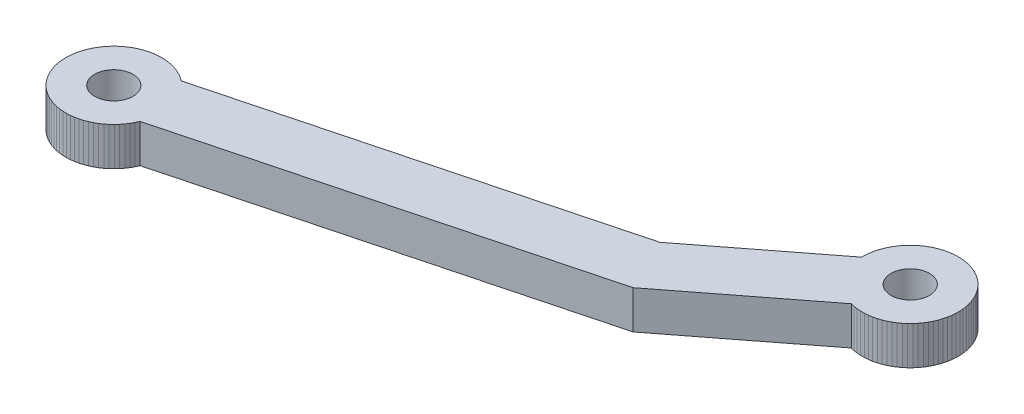
SolidWorks part; units mm, degrees
ref_plane "Спереди" through (0, 0, 0) normal (0, 0, 1) x (1, 0, 0)
ref_plane "Сверху" through (0, 0, 0) normal (0, 1, 0) x (1, 0, 0)
ref_plane "Справа" through (0, 0, 0) normal (1, 0, 0) x (0, 0, -1)
ref_plane "Плоскость4" through (0, -23, 0) normal (0, -1, 0) x (1, 0, 0)
sketch "Эскиз1" plane through (0, -23, 0) normal (0, -1, 0) x (1, 0, 0)
  line L0 (-84.0281, -2.2024) -> (-83.8528, -2.288)
  line L1 (-83.8528, -2.288) -> (-83.6713, -2.3596)
  line L2 (-83.6713, -2.3596) -> (-83.4847, -2.4168)
  line L3 (-83.4847, -2.4168) -> (-83.2943, -2.4593)
  line L4 (-83.2943, -2.4593) -> (-83.1011, -2.4869)
  line L5 (-83.1011, -2.4869) -> (-82.9064, -2.4993)
  line L6 (-82.9064, -2.4993) -> (-82.7113, -2.4964)
  line L7 (-82.7113, -2.4964) -> (-82.517, -2.4784)
  line L8 (-82.517, -2.4784) -> (-82.3248, -2.4452)
  line L9 (-82.3248, -2.4452) -> (-82.1357, -2.3972)
  line L10 (-82.1357, -2.3972) -> (-81.9509, -2.3346)
  line L11 (-81.9509, -2.3346) -> (-81.7715, -2.2577)
  line L12 (-81.7715, -2.2577) -> (-81.5987, -2.1671)
  line L13 (-81.5987, -2.1671) -> (-81.4335, -2.0633)
  line L14 (-81.4335, -2.0633) -> (-81.2769, -1.9469)
  line L15 (-81.2769, -1.9469) -> (-81.1299, -1.8187)
  line L16 (-81.1299, -1.8187) -> (-80.9933, -1.6794)
  line L17 (-80.9933, -1.6794) -> (-80.8679, -1.5298)
  line L18 (-80.8679, -1.5298) -> (-80.7546, -1.371)
  line L19 (-80.7546, -1.371) -> (-80.6541, -1.2038)
  line L20 (-80.6541, -1.2038) -> (-80.5669, -1.0292)
  line L21 (-80.5669, -1.0292) -> (-80.4936, -0.8484)
  line L22 (-80.4936, -0.8484) -> (-80.4346, -0.6624)
  line L23 (-80.4346, -0.6624) -> (-80.3902, -0.4724)
  line L24 (-80.3902, -0.4724) -> (-80.3609, -0.2795)
  line L25 (-80.3609, -0.2795) -> (-80.3466, -0.0849)
  line L26 (-80.3466, -0.0849) -> (-80.3476, 0.1102)
  line L27 (-80.3476, 0.1102) -> (-80.3638, 0.3046)
  line L28 (-80.3638, 0.3046) -> (-80.3951, 0.4972)
  line L29 (-80.3951, 0.4972) -> (-80.4414, 0.6868)
  line L30 (-80.4414, 0.6868) -> (-80.5022, 0.8721)
  line L31 (-80.5022, 0.8721) -> (-80.5774, 1.0522)
  line L32 (-80.5774, 1.0522) -> (-80.6664, 1.2258)
  line L33 (-80.6664, 1.2258) -> (-80.7686, 1.392)
  line L34 (-80.7686, 1.392) -> (-80.8835, 1.5497)
  line L35 (-80.8835, 1.5497) -> (-81.0103, 1.698)
  line L36 (-81.0103, 1.698) -> (-81.1483, 1.8359)
  line L37 (-81.1483, 1.8359) -> (-81.2967, 1.9627)
  line L38 (-81.2967, 1.9627) -> (-81.4544, 2.0774)
  line L39 (-81.4544, 2.0774) -> (-81.6207, 2.1796)
  line L40 (-81.6207, 2.1796) -> (-81.7944, 2.2684)
  line L41 (-81.7944, 2.2684) -> (-81.9745, 2.3435)
  line L42 (-81.9745, 2.3435) -> (-82.1599, 2.4042)
  line L43 (-82.1599, 2.4042) -> (-82.3495, 2.4504)
  line L44 (-82.3495, 2.4504) -> (-82.5421, 2.4816)
  line L45 (-82.5421, 2.4816) -> (-82.7365, 2.4976)
  line L46 (-82.7365, 2.4976) -> (-82.9317, 2.4985)
  line L47 (-82.9317, 2.4985) -> (-83.1262, 2.4842)
  line L48 (-83.1262, 2.4842) -> (-83.3191, 2.4547)
  line L49 (-83.3191, 2.4547) -> (-83.5091, 2.4102)
  line L50 (-83.5091, 2.4102) -> (-89.9237, 7.3733)
  line L51 (-89.9237, 7.3733) -> (-110.2847, 12.7181)
  line L52 (-110.2847, 12.7181) -> (-110.3653, 12.8958)
  line L53 (-110.3653, 12.8958) -> (-110.4595, 13.0666)
  line L54 (-110.4595, 13.0666) -> (-110.5667, 13.2296)
  line L55 (-110.5667, 13.2296) -> (-110.6864, 13.3838)
  line L56 (-110.6864, 13.3838) -> (-110.8177, 13.5281)
  line L57 (-110.8177, 13.5281) -> (-110.9598, 13.6618)
  line L58 (-110.9598, 13.6618) -> (-111.1119, 13.7839)
  line L59 (-111.1119, 13.7839) -> (-111.2731, 13.8939)
  line L60 (-111.2731, 13.8939) -> (-111.4424, 13.9909)
  line L61 (-111.4424, 13.9909) -> (-111.6187, 14.0744)
  line L62 (-111.6187, 14.0744) -> (-111.8011, 14.1439)
  line L63 (-111.8011, 14.1439) -> (-111.9882, 14.199)
  line L64 (-111.9882, 14.199) -> (-112.1791, 14.2393)
  line L65 (-112.1791, 14.2393) -> (-112.3726, 14.2647)
  line L66 (-112.3726, 14.2647) -> (-112.5674, 14.2748)
  line L67 (-112.5674, 14.2748) -> (-112.7625, 14.2697)
  line L68 (-112.7625, 14.2697) -> (-112.9565, 14.2495)
  line L69 (-112.9565, 14.2495) -> (-113.1484, 14.2141)
  line L70 (-113.1484, 14.2141) -> (-113.337, 14.1639)
  line L71 (-113.337, 14.1639) -> (-113.521, 14.0992)
  line L72 (-113.521, 14.0992) -> (-113.6995, 14.0203)
  line L73 (-113.6995, 14.0203) -> (-113.8712, 13.9277)
  line L74 (-113.8712, 13.9277) -> (-114.0352, 13.822)
  line L75 (-114.0352, 13.822) -> (-114.1905, 13.7038)
  line L76 (-114.1905, 13.7038) -> (-114.3361, 13.5739)
  line L77 (-114.3361, 13.5739) -> (-114.4711, 13.4331)
  line L78 (-114.4711, 13.4331) -> (-114.5947, 13.2821)
  line L79 (-114.5947, 13.2821) -> (-114.7061, 13.1219)
  line L80 (-114.7061, 13.1219) -> (-114.8048, 12.9536)
  line L81 (-114.8048, 12.9536) -> (-114.89, 12.7781)
  line L82 (-114.89, 12.7781) -> (-114.9612, 12.5964)
  line L83 (-114.9612, 12.5964) -> (-115.0181, 12.4098)
  line L84 (-115.0181, 12.4098) -> (-115.0602, 12.2193)
  line L85 (-115.0602, 12.2193) -> (-115.0874, 12.0261)
  line L86 (-115.0874, 12.0261) -> (-115.0994, 11.8313)
  line L87 (-115.0994, 11.8313) -> (-115.0961, 11.6362)
  line L88 (-115.0961, 11.6362) -> (-115.0777, 11.442)
  line L89 (-115.0777, 11.442) -> (-115.0442, 11.2498)
  line L90 (-115.0442, 11.2498) -> (-114.9958, 11.0608)
  line L91 (-114.9958, 11.0608) -> (-114.9328, 10.8761)
  line L92 (-114.9328, 10.8761) -> (-114.8556, 10.6969)
  line L93 (-114.8556, 10.6969) -> (-114.7646, 10.5243)
  line L94 (-114.7646, 10.5243) -> (-114.6605, 10.3593)
  line L95 (-114.6605, 10.3593) -> (-114.5438, 10.2029)
  line L96 (-114.5438, 10.2029) -> (-114.4153, 10.0561)
  line L97 (-114.4153, 10.0561) -> (-114.2757, 9.9198)
  line L98 (-114.2757, 9.9198) -> (-114.1259, 9.7947)
  line L99 (-114.1259, 9.7947) -> (-113.9668, 9.6818)
  line L100 (-113.9668, 9.6818) -> (-113.7994, 9.5815)
  line L101 (-113.7994, 9.5815) -> (-113.6247, 9.4947)
  line L102 (-113.6247, 9.4947) -> (-113.4438, 9.4217)
  line L103 (-113.4438, 9.4217) -> (-113.2577, 9.3631)
  line L104 (-113.2577, 9.3631) -> (-113.0676, 9.3191)
  line L105 (-113.0676, 9.3191) -> (-112.8746, 9.2902)
  line L106 (-112.8746, 9.2902) -> (-112.68, 9.2763)
  line L107 (-112.68, 9.2763) -> (-112.4849, 9.2777)
  line L108 (-112.4849, 9.2777) -> (-112.2905, 9.2943)
  line L109 (-112.2905, 9.2943) -> (-112.098, 9.326)
  line L110 (-112.098, 9.326) -> (-111.9085, 9.3726)
  line L111 (-111.9085, 9.3726) -> (-111.7232, 9.4338)
  line L112 (-111.7232, 9.4338) -> (-111.5433, 9.5093)
  line L113 (-111.5433, 9.5093) -> (-111.3698, 9.5986)
  line L114 (-111.3698, 9.5986) -> (-111.2039, 9.7012)
  line L115 (-111.2039, 9.7012) -> (-111.0464, 9.8164)
  line L116 (-111.0464, 9.8164) -> (-91.2763, 4.6267)
  line L117 (-91.2763, 4.6267) -> (-85.3449, 0.0375)
  line L118 (-85.3449, 0.0375) -> (-85.3402, -0.1575)
  line L119 (-85.3402, -0.1575) -> (-85.3203, -0.3516)
  line L120 (-85.3203, -0.3516) -> (-85.2854, -0.5436)
  line L121 (-85.2854, -0.5436) -> (-85.2356, -0.7322)
  line L122 (-85.2356, -0.7322) -> (-85.1712, -0.9164)
  line L123 (-85.1712, -0.9164) -> (-85.0926, -1.095)
  line L124 (-85.0926, -1.095) -> (-85.0004, -1.267)
  line L125 (-85.0004, -1.267) -> (-84.895, -1.4312)
  line L126 (-84.895, -1.4312) -> (-84.7771, -1.5867)
  line L127 (-84.7771, -1.5867) -> (-84.6475, -1.7325)
  line L128 (-84.6475, -1.7325) -> (-84.5069, -1.8678)
  line L129 (-84.5069, -1.8678) -> (-84.3562, -1.9917)
  line L130 (-84.3562, -1.9917) -> (-84.1963, -2.1035)
  line L131 (-84.1963, -2.1035) -> (-84.0281, -2.2024)
  circle A0 centre (-82.8452, 0) radius 1
  circle A1 centre (-112.6, 11.775) radius 1
extrude "Бобышка-Вытянуть1" add sketch "Эскиз1" against normal blind 2
